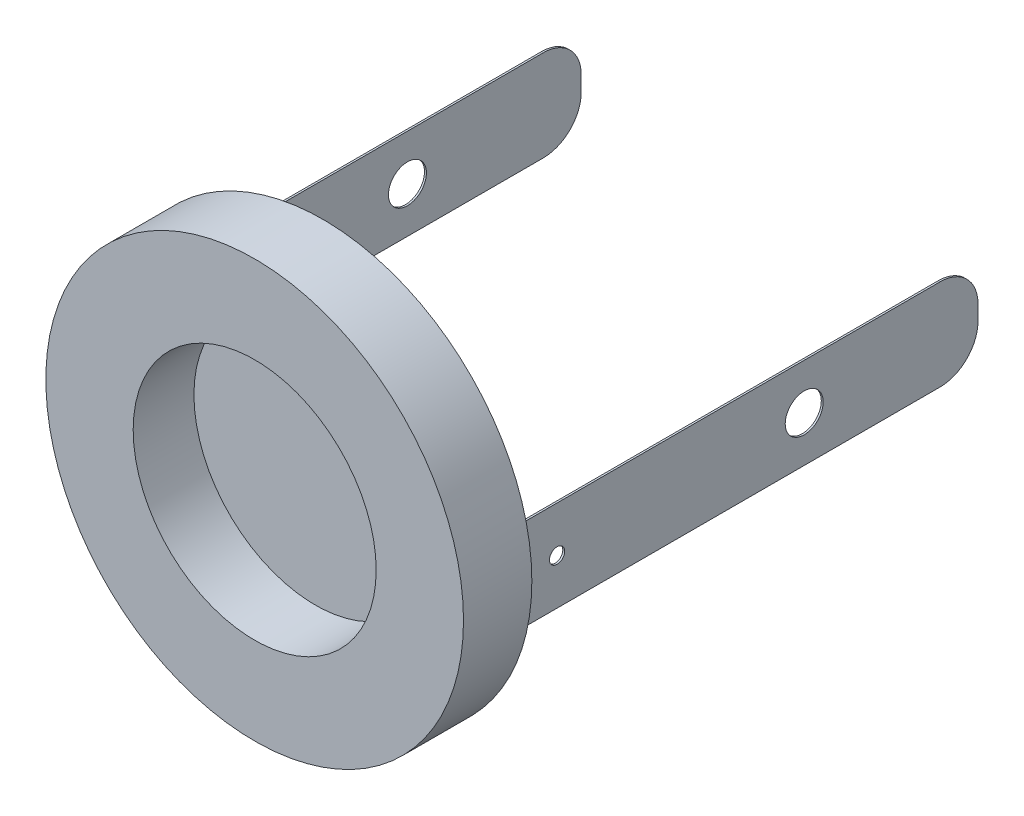
SolidWorks part; units mm, degrees
ref_plane "Front Plane" through (0, 0, 0) normal (0, 0, 1) x (1, 0, 0)
ref_plane "Top Plane" through (0, 0, 0) normal (0, 1, 0) x (1, 0, 0)
ref_plane "Right Plane" through (0, 0, 0) normal (1, 0, 0) x (0, 0, -1)
sketch "Sketch1" plane through (0, 0, 0) normal (0, 0, 1) x (1, 0, 0)
  circle A0 centre (0, 0) radius 27.5
  dimension "D1" = 55
extrude "Boss-Extrude1" add sketch "Sketch1" along normal blind 1
sketch "Sketch2" plane through (0, 0, 1) normal (0, 0, 1) x (1, 0, 0)
  circle A0 centre (0, 0) radius 16
  circle A1 centre (0, 0) radius 27.5
  dimension "D1" = 55
  dimension "D2" = 32
extrude "Boss-Extrude2" add sketch "Sketch2" along normal blind 8
sketch "Sketch3" plane through (0, 0, 0) normal (0, 0, -1) x (-1, 0, 0)
  line L0 (-10.9886, 0) -> (10.4466, 0) construction
  line L1 (0, 10.2261) -> (0, -10.3215) construction
  line L2 (-26.2503, -6) -> (-26.2503, 6)
  line L3 (-26, -6) -> (-26, 6)
  line L4 (-26, 6) -> (-26.2503, 6)
  line L5 (-26, -6) -> (-26.2503, -6)
  line L6 (26, -6) -> (26.2503, -6)
  line L7 (26, 6) -> (26.2503, 6)
  line L8 (26.2503, -6) -> (26.2503, 6)
  line L9 (26, -6) -> (26, 6)
  point P13 (-26.2503, 0)
  point P14 (-26, 0)
  dimension "D1" = 26
  dimension "D3" = 6
extrude "Boss-Extrude3" add sketch "Sketch3" along normal blind 60
sketch "Sketch4" plane through (0, 0, 0) normal (1, 0, 0) x (0, 0, -1)
  circle A0 centre (37.1139, 0) radius 2.5
  circle A1 centre (4.5732, 0) radius 1
  point P2 (16.7023, 0)
  point P3 (13.8225, 0)
  point P4 (8.2794, 0)
  point P5 (53.9767, 0)
  point P8 (26.2407, 0)
  point P9 (9.9583, 0)
  point P10 (4.5732, 0)
  dimension "D1" = 5
  dimension "D2" = 2
extrude "Cut-Extrude1" cut sketch "Sketch4" against normal through all both and the other way through all
fillet "Fillet1" radius 5 4 edges at (-26.1252, 6, -60) (-26.1252, -6, -60) (26.1252, 6, -60) (26.1252, -6, -60)
